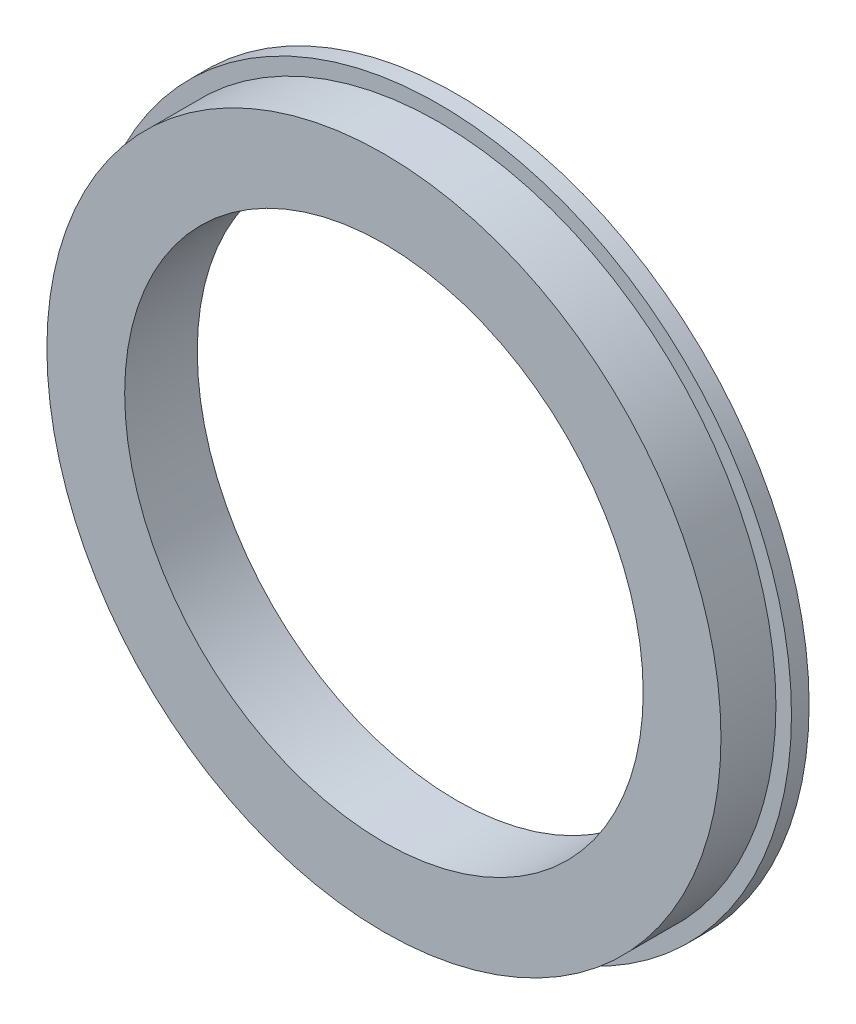
SolidWorks part; units mm, degrees
material "1.5714 (16NiCr4)"
ref_plane "前视基准面" through (0, 0, 0) normal (0, 0, 1) x (1, 0, 0)
ref_plane "上视基准面" through (0, 0, 0) normal (0, 1, 0) x (1, 0, 0)
ref_plane "右视基准面" through (0, 0, 0) normal (1, 0, 0) x (0, 0, -1)
sketch "草图1" plane through (0, 0, 0) normal (0, 0, 1) x (1, 0, 0)
  circle A0 centre (0, 0) radius 32.5
  circle A1 centre (0, 0) radius 25
  dimension "D1" = 65
  dimension "D2" = 50
extrude "凸台-拉伸1" add sketch "草图1" along normal blind 7
sketch "草图2" plane through (0, 0, 0) normal (0, 0, 1) x (1, 0, 0)
  circle A0 centre (0, 0) radius 34
  circle A1 centre (0, 0) radius 32.5 construction
  circle A2 centre (0, 0) radius 32.5
  dimension "D1" = 68
extrude "凸台-拉伸2" add sketch "草图2" along normal blind 1.7
